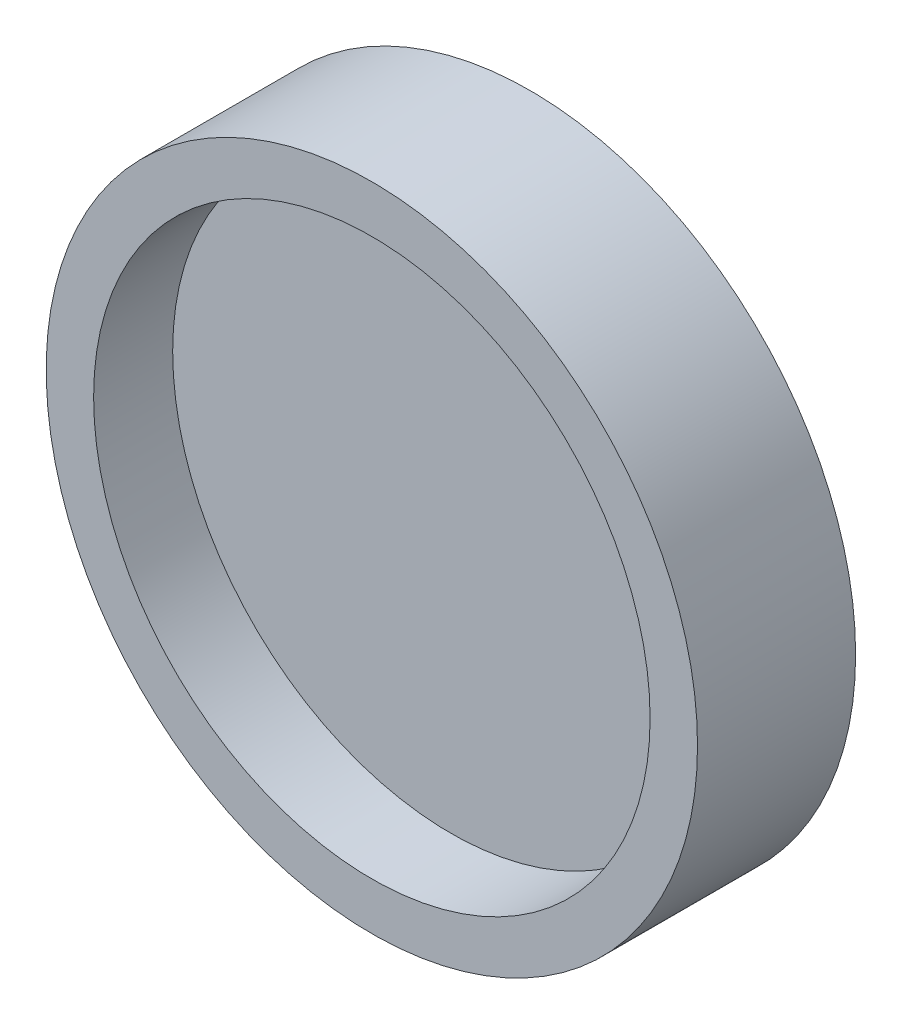
SolidWorks part; units mm, degrees
ref_plane "前视基准面" through (0, 0, 0) normal (0, 0, 1) x (1, 0, 0)
ref_plane "上视基准面" through (0, 0, 0) normal (0, 1, 0) x (1, 0, 0)
ref_plane "右视基准面" through (0, 0, 0) normal (1, 0, 0) x (0, 0, -1)
sketch "草图1" plane through (0, 0, 0) normal (0, 0, 1) x (1, 0, 0)
  circle A0 centre (0, 0) radius 41.2
extrude "凸台-拉伸1" add sketch "草图1" along normal blind 20
sketch "草图2" plane through (0, 0, 20) normal (0, 0, 1) x (1, 0, 0)
  circle A0 centre (0, 0) radius 35.2
extrude "切除-拉伸1" cut sketch "草图2" against normal blind 10
sketch "草图3" plane through (0, 0, 20) normal (0, 0, 1) x (1, 0, 0)
  line L0 (0, 41.2) -> (0, -41.2)
  circle A0 centre (0, 0) radius 41.2 construction
